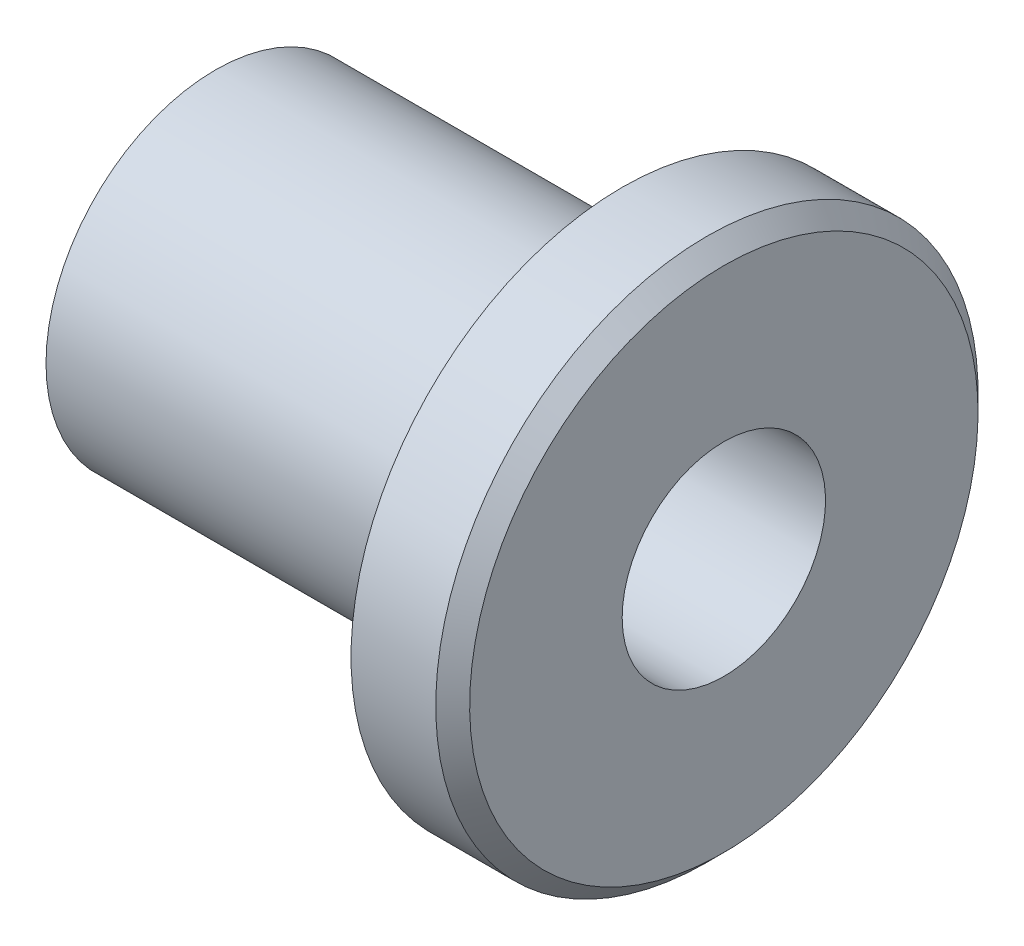
SolidWorks part; units mm, degrees
ref_plane "Front" through (0, 0, 0) normal (0, 0, 1) x (1, 0, 0)
ref_plane "Top" through (0, 0, 0) normal (0, 1, 0) x (1, 0, 0)
ref_plane "Right" through (0, 0, 0) normal (1, 0, 0) x (0, 0, -1)
sketch "草图1" plane through (0, 0, 0) normal (0, 0, 1) x (1, 0, 0)
  line L0 (-9.4286, 0) -> (-9.4286, 5)
  line L1 (-9.4286, 5) -> (2.5714, 5)
  line L2 (2.5714, 5) -> (2.5714, 8)
  line L3 (2.5714, 8) -> (5.5714, 8)
  line L4 (5.5714, 8) -> (5.5714, 0)
  line L5 (5.5714, 0) -> (-9.4286, 0)
  dimension "D1" = 3
  dimension "D2" = 5
  dimension "D3" = 8
  dimension "D4" = 15
revolve "旋转1" add sketch "草图1" angle 360 about L5
hole_wizard "Ø6.0 (6) 直径孔1" positions "草图4" profile "草图5" hole size "Ø6.0" standard "GB"
sketch "草图4" plane through (-9.4286, 0, 0) normal (-1, 0, 0) x (0, 0, 1)
  point P0 (0, 0)
sketch "草图5" plane through (-9.4286, 0, 0) normal (0, 1, 0) x (0, 0, 1)
  line L0 (0, 0) -> (0, 20)
  line L1 (0, 20) -> (3, 18.1974)
  line L2 (3, 18.1974) -> (3, 0)
  line L5 (3, 0) -> (0, 0)
  line L10 (0, 20) -> (-3, 18.1974) construction
  line L11 (0, -6.35) -> (0, 107.95) construction
  dimension "孔直径" = 6
  dimension "孔深度" = 20
  dimension "导头角度" = 118
chamfer "倒角1" distance 0.5 angle 45 1 edges at (5.5714, 8, 0)
